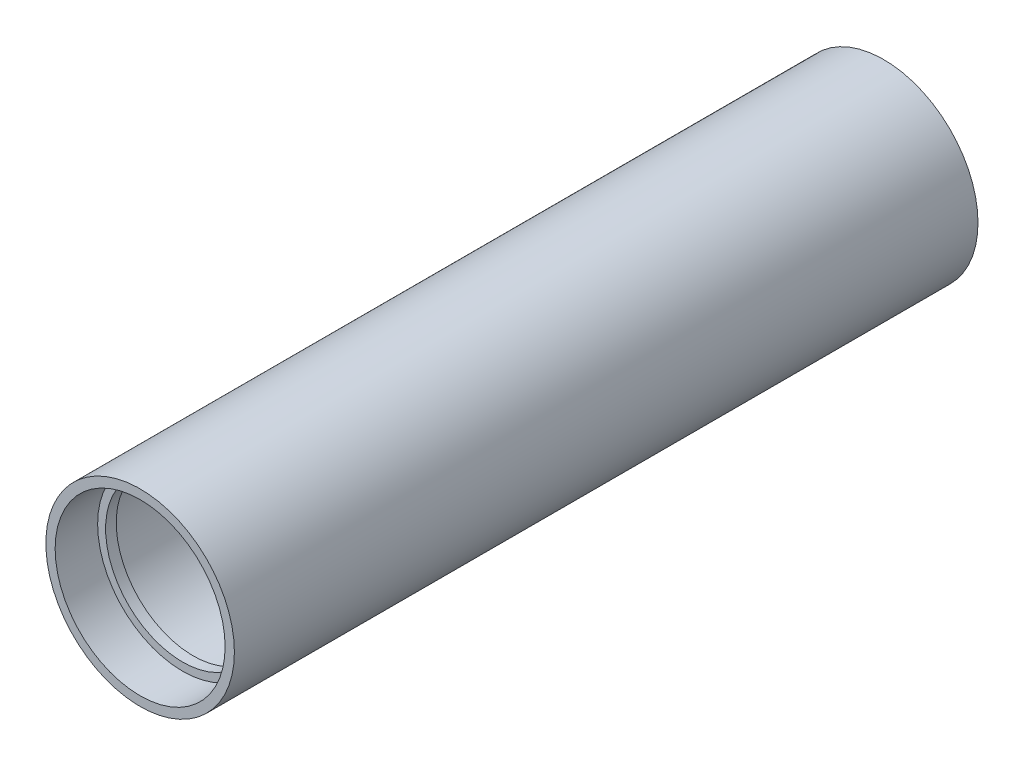
SolidWorks part; units mm, degrees
material "6061 Alloy"
ref_plane "Front Plane" through (0, 0, 0) normal (0, 0, 1) x (1, 0, 0)
ref_plane "Top Plane" through (0, 0, 0) normal (0, 1, 0) x (1, 0, 0)
ref_plane "Right Plane" through (0, 0, 0) normal (1, 0, 0) x (0, 0, -1)
sketch "Sketch1" plane through (0, 0, 0) normal (0, 0, 1) x (1, 0, 0)
  circle A0 centre (0, 0) radius 17.75
  circle A1 centre (0, 0) radius 16
  dimension "Bore" = 32
  dimension "D1" = 35.5
extrude "Boss-Extrude1" add sketch "Sketch1" along normal mid plane 140
sketch "Sketch2" plane through (0, 0, 0) normal (0, 0, 1) x (1, 0, 0)
  circle A0 centre (0, 0) radius 14.5
  circle A1 centre (0, 0) radius 16
  dimension "D1" = 32
  dimension "D2" = 29
extrude "Boss-Extrude2" add sketch "Sketch2" along normal blind 2 from offset 60
mirror "Mirror1" about plane through (0, 0, 0) normal (0, 0, 1) of "Boss-Extrude2"
sketch "Sketch3" plane through (0, 0, 0) normal (0, 1, 0) x (1, 0, 0)
  line L0 (0, 50) -> (0, -50) construction
  line L1 (0, 35) -> (0, -35) construction
  line L2 (-8, 0) -> (8, 0) construction
  line L3 (19.75, 0) -> (-19.75, 0) construction
  point P4 (0, 0)
  point P8 (0, 0)
  point P11 (0, 0)
  point P13 (0, 0)
  dimension "Stroke" = 100
  dimension "C" = 70
  dimension "G" = 16
equation "\"D2@Sketch2\"=\"D1@Sketch2\"-3"
equation "\"D19@Boss-Extrude2\"=\"Stroke\"/2 +10"
equation "\"D1@Boss-Extrude1\"=\"C@Sketch3\"+\"Stroke\"-2*\"G@Sketch3\"+2"
equation "\"D1@Sketch1\"=\"U@Sketch3\"-4"
equation "\"D1@Sketch2\"=\"Bore@Sketch1\""
equation "\"Stroke\"= 100'Standard Strole [25 50 75 80 100 125 150 160 175 200 250 300 350 400 450 500]"
equation "\"Stroke@Sketch3\"=\"Stroke\""
